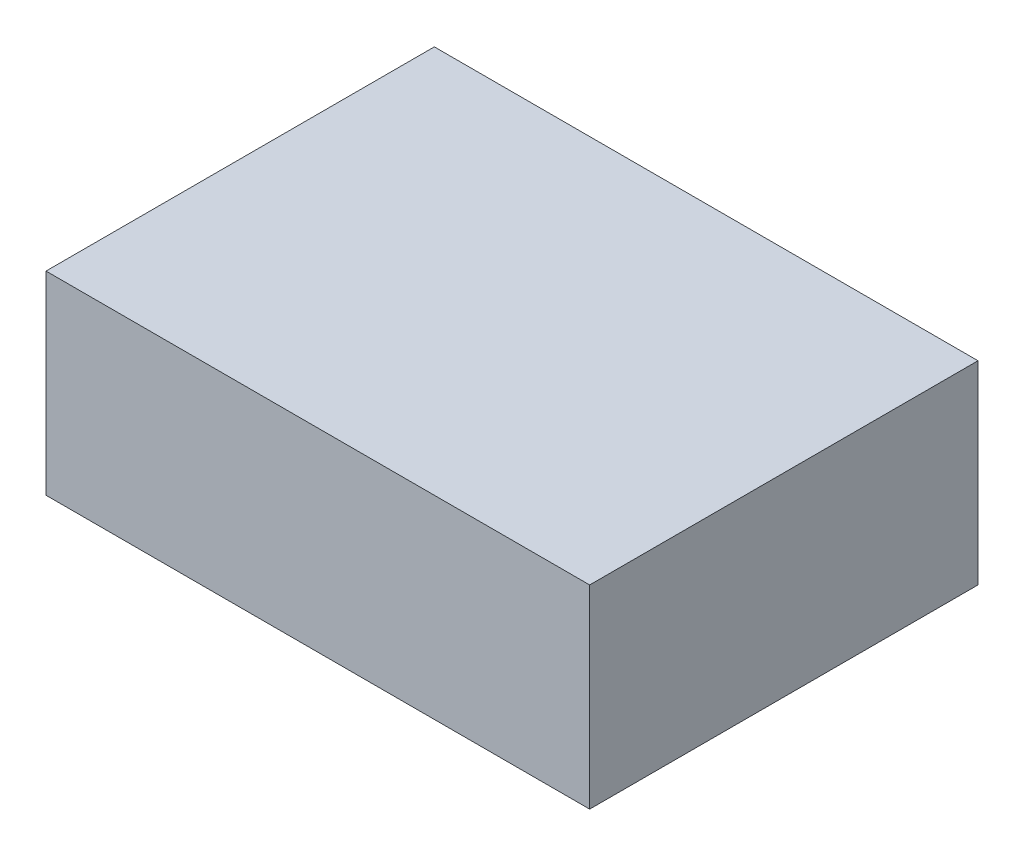
SolidWorks part; units mm, degrees
ref_plane "Front Plane" through (0, 0, 0) normal (0, 0, 1) x (1, 0, 0)
ref_plane "Top Plane" through (0, 0, 0) normal (0, 1, 0) x (1, 0, 0)
ref_plane "Right Plane" through (0, 0, 0) normal (1, 0, 0) x (0, 0, -1)
sketch "Sketch1" plane through (0, 0, 0) normal (0, 1, 0) x (1, 0, 0)
  line L1 (-0.7, -0.5) -> (0.7, -0.5)
  line L2 (-0.7, -0.5) -> (-0.7, 0.5)
  line L3 (-0.7, 0.5) -> (0.7, 0.5)
  line L4 (0.7, -0.5) -> (0.7, 0.5)
  line L5 (-0.7, -0.5) -> (0.7, 0.5) construction
  line L6 (-0.7, 0.5) -> (0.7, -0.5) construction
  point P0 (0, 0)
  dimension "D1" = 1.4
  dimension "D2" = 1
extrude "Boss-Extrude1" add sketch "Sketch1" along normal blind 0.5
